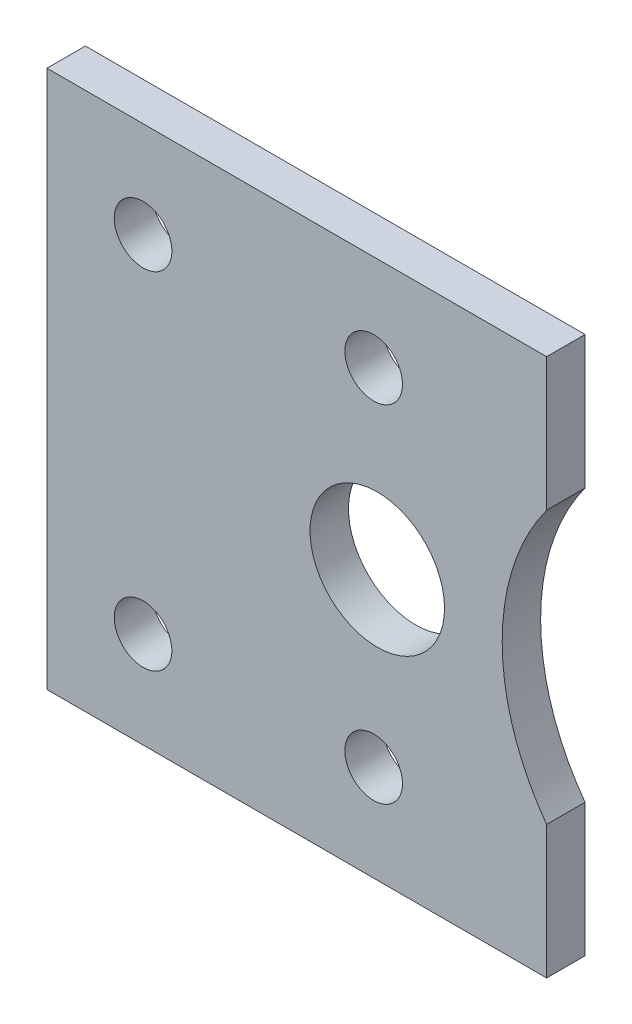
SolidWorks part; units mm, degrees
ref_plane "Płaszczyzna przednia" through (0, 0, 0) normal (0, 0, 1) x (1, 0, 0)
ref_plane "Płaszczyzna górna" through (0, 0, 0) normal (0, 1, 0) x (1, 0, 0)
ref_plane "Płaszczyzna prawa" through (0, 0, 0) normal (1, 0, 0) x (0, 0, -1)
sketch "Szkic1" plane through (0, 0, 0) normal (0, 0, 1) x (1, 0, 0)
  line L0 (0, 0) -> (0, 28)
  line L1 (0, 28) -> (26, 28)
  line L2 (26, 28) -> (26, 21.0802)
  line L3 (0, 0) -> (26, 0)
  line L4 (26, 0) -> (26, 6.9198)
  line L5 (0, 14) -> (57.7498, 14) construction
  arc A0 (26, 21.0802) -> (26, 6.9198) centre (35.6887, 14) ccw
  circle A1 centre (17.1887, 14) radius 3.5
  circle A2 centre (17, 5) radius 1.5
  circle A3 centre (5, 5) radius 1.5
  circle A4 centre (17, 23) radius 1.5
  circle A5 centre (5, 23) radius 1.5
  point P10 (23.6887, 14)
  point P11 (20.6887, 14)
  point P18 (0, 0)
  dimension "D3" = 12
  dimension "D5" = 7
  dimension "D6" = 3
  dimension "D7" = 3
  dimension "D8" = 3
  dimension "D1" = 28
  dimension "D2" = 26
  dimension "D4" = 35.6887
  dimension "D9" = 5
  dimension "D10" = 17
  dimension "D11" = 5
extrude "Dodanie-wyciągnięcie1" add sketch "Szkic1" along normal blind 2
